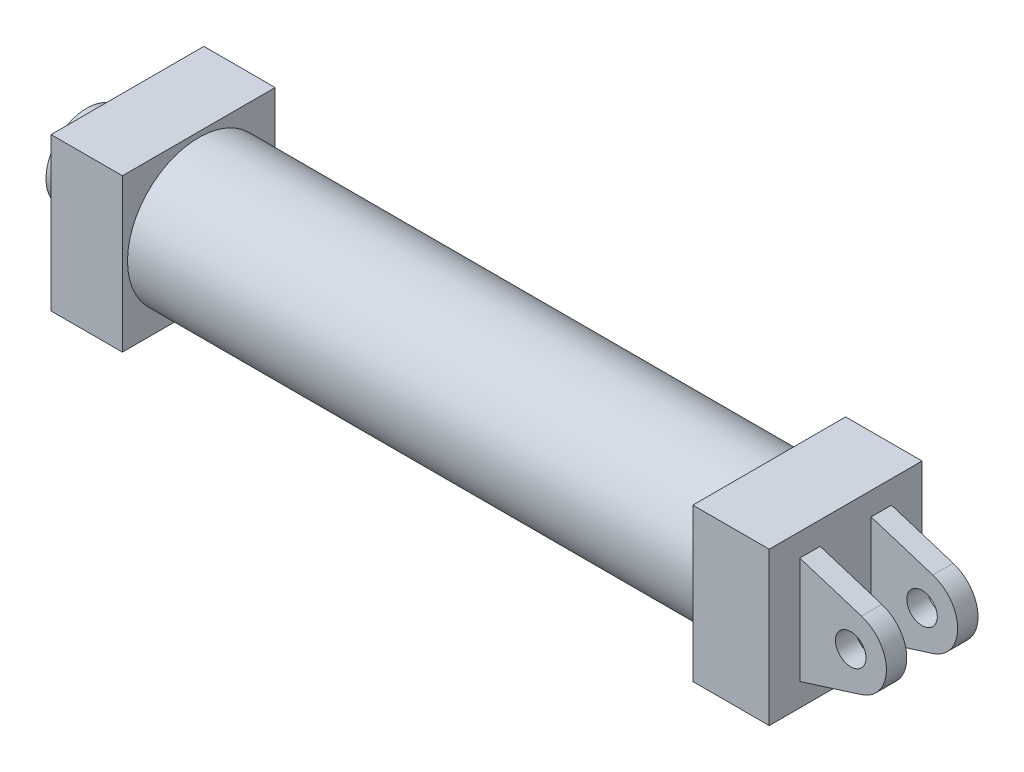
SolidWorks part; units mm, degrees
material "PW50:4:Ar:0:-1:C1:1:2:3:Re:11:"
ref_plane "front" through (0, 0, 0) normal (0, 0, 1) x (1, 0, 0)
ref_plane "top" through (0, 0, 0) normal (0, 1, 0) x (1, 0, 0)
ref_plane "side" through (0, 0, 0) normal (1, 0, 0) x (0, 0, -1)
sketch "Sketch1" plane through (0, 0, 0) normal (1, 0, 0) x (0, 0, -1)
  line L0 (-47.625, 47.625) -> (47.625, 47.625)
  line L1 (-47.625, 47.625) -> (-47.625, -47.625)
  line L2 (47.625, -47.625) -> (-47.625, -47.625)
  line L3 (47.625, -47.625) -> (47.625, 47.625)
  line L4 (0, 47.625) -> (0, 0) construction
  line L5 (47.625, 0) -> (0, 0) construction
  dimension "D1" = 95.25
extrude "Base-Extrude" add sketch "Sketch1" against normal blind 47.625
sketch "Sketch2" plane through (-47.625, 0, 0) normal (-1, 0, 0) x (0, 0, 1)
  circle A0 centre (0, 0) radius 44.45
  dimension "D1" = 88.9
extrude "Boss-Extrude1" add sketch "Sketch2" along normal blind 355.6
sketch "Sketch3" plane through (-403.225, 0, 0) normal (-1, 0, 0) x (0, 0, 1)
  line L4 (47.625, -47.625) -> (47.625, 47.625)
  line L5 (47.625, 47.625) -> (-47.625, 47.625)
  line L6 (-47.625, 47.625) -> (-47.625, -47.625)
  line L7 (-47.625, -47.625) -> (47.625, -47.625)
  line L8 (47.625, -47.625) -> (47.625, 47.625)
  line L9 (47.625, 47.625) -> (-47.625, 47.625)
  line L10 (-47.625, 47.625) -> (-47.625, -47.625)
  line L11 (-47.625, -47.625) -> (47.625, -47.625)
  dimension "D1" = 0
extrude "Boss-Extrude2" add sketch "Sketch3" along normal blind 44.45
sketch "Sketch4" plane through (-447.675, 0, 0) normal (-1, 0, 0) x (0, 0, 1)
  circle A0 centre (0, 0) radius 25.4
  dimension "D1" = 50.8
extrude "Boss-Extrude3" add sketch "Sketch4" along normal blind 25.4
sketch "Sketch5" plane through (-473.075, 0, 0) normal (-1, 0, 0) x (0, 0, 1)
  circle A0 centre (0, 0) radius 17.4625
  dimension "D1" = 34.925
extrude "Cut-Extrude1" cut sketch "Sketch5" against normal up to surface (425.45 mm away)
sketch "Sketch6" plane through (0, 0, 0) normal (0, 0, 1) x (1, 0, 0)
  line L0 (0, 0) -> (31.75, 0) construction
  line L1 (-403.225, 0) -> (-47.625, 0) construction
  line L2 (38.4332, 21.1964) -> (0, 33.3143)
  line L3 (0, 47.625) -> (0, -47.625) construction
  line L4 (38.4332, -21.1964) -> (0, -33.3143)
  line L5 (0, 33.3143) -> (0, -33.3143)
  arc A0 (38.4332, -21.1964) -> (38.4332, 21.1964) centre (31.75, 0) ccw
  circle A1 centre (31.75, 0) radius 9.525
  dimension "D3" = 19.05
  dimension "D4" = 22.225
  dimension "D1" = 35
  dimension "D2" = 31.75
extrude "Boss-Extrude4" add sketch "Sketch6" along normal mid plane 57.15
sketch "Sketch7" plane through (0, 47.625, 0) normal (0, 1, 0) x (-1, 0, 0)
  line L0 (0, 0) -> (-73.3102, 0) construction
  line L1 (403.225, 0) -> (47.625, 0) construction
  line L2 (-53.975, 15.875) -> (-53.975, -15.875)
  line L3 (-53.975, -15.875) -> (0, -15.875)
  line L4 (0, 47.625) -> (0, -47.625) construction
  line L5 (-53.975, 15.875) -> (0, 15.875)
  line L6 (0, -15.875) -> (0, 15.875)
  line L7 (-53.975, 28.575) -> (-53.975, -28.575) construction
  point P8 (-53.975, 0)
  point P12 (0, 0)
  dimension "D1" = 31.75
extrude "Cut-Extrude2" cut sketch "Sketch7" against normal through all
